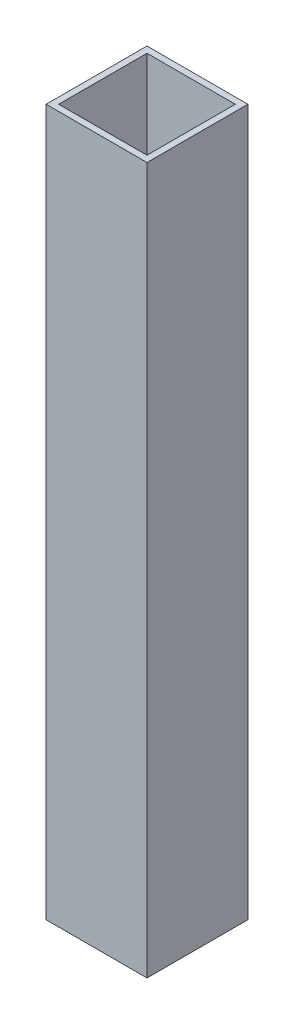
SolidWorks part; units mm, degrees
material "6061 Alloy"
ref_plane "Front Plane" through (0, 0, 0) normal (0, 0, 1) x (1, 0, 0)
ref_plane "Top Plane" through (0, 0, 0) normal (0, 1, 0) x (1, 0, 0)
ref_plane "Right Plane" through (0, 0, 0) normal (1, 0, 0) x (0, 0, -1)
sketch "Sketch1" plane through (0, 0, 0) normal (0, 1, 0) x (1, 0, 0)
  line L1 (12.7, -12.7) -> (-12.7, -12.7)
  line L2 (12.7, -12.7) -> (12.7, 12.7)
  line L3 (12.7, 12.7) -> (-12.7, 12.7)
  line L4 (-12.7, -12.7) -> (-12.7, 12.7)
  line L5 (12.7, -12.7) -> (-12.7, 12.7) construction
  line L6 (12.7, 12.7) -> (-12.7, -12.7) construction
  line L7 (11.1125, -11.1125) -> (-11.1125, -11.1125)
  line L8 (11.1125, -11.1125) -> (11.1125, 11.1125)
  line L9 (11.1125, 11.1125) -> (-11.1125, 11.1125)
  line L10 (-11.1125, -11.1125) -> (-11.1125, 11.1125)
  line L11 (11.1125, -11.1125) -> (-11.1125, 11.1125) construction
  line L12 (11.1125, 11.1125) -> (-11.1125, -11.1125) construction
  point P0 (0, 0)
  point P6 (0, 0)
  dimension "D1" = 25.4
  dimension "D2" = 25.4
  dimension "D3" = 1.5875
extrude "Boss-Extrude1" add sketch "Sketch1" along normal blind 177.8
